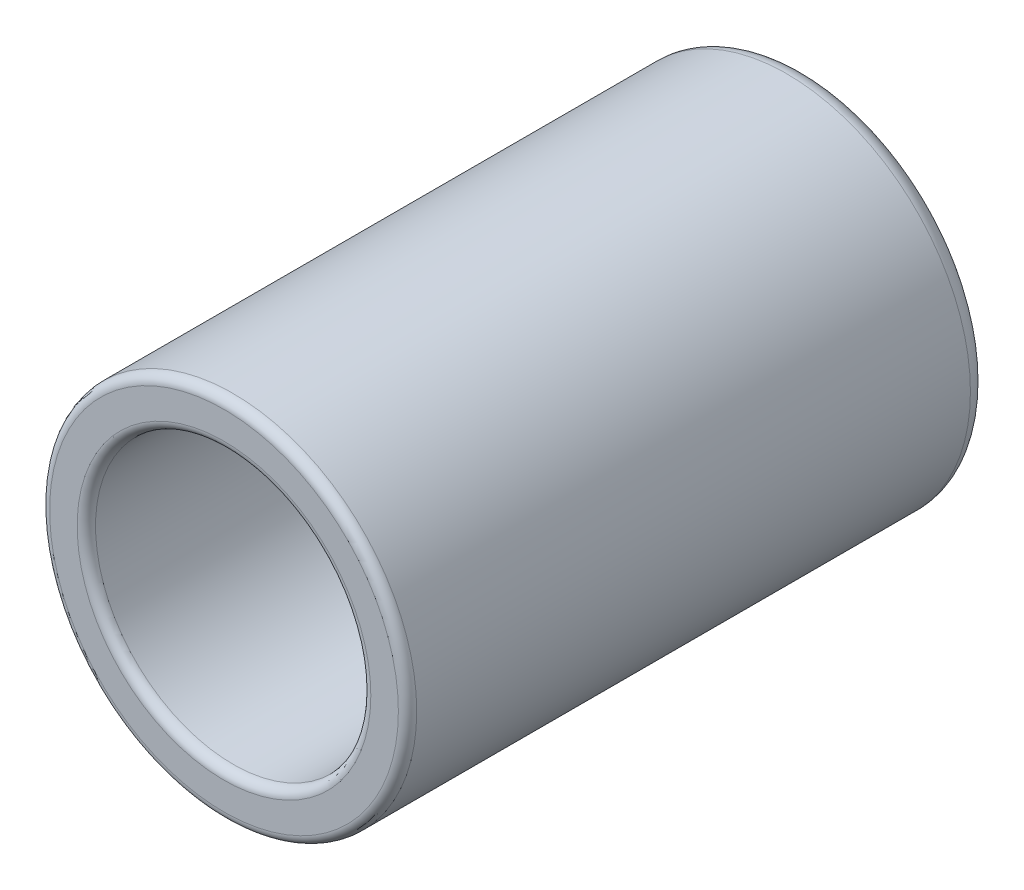
SolidWorks part; units mm, degrees
ref_plane "Płaszczyzna przednia" through (0, 0, 0) normal (0, 0, 1) x (1, 0, 0)
ref_plane "Płaszczyzna górna" through (0, 0, 0) normal (0, 1, 0) x (1, 0, 0)
ref_plane "Płaszczyzna prawa" through (0, 0, 0) normal (1, 0, 0) x (0, 0, -1)
sketch "Sketch1" plane through (0, 0, 0) normal (0, 0, 1) x (1, 0, 0)
  circle A0 centre (0, 0) radius 3
  dimension "D1" = 6
extrude "Boss-Extrude1" add sketch "Sketch1" along normal blind 9.5
sketch "Sketch2" plane through (0, 0, 9.5) normal (0, 0, 1) x (1, 0, 0)
  circle A0 centre (0, 0) radius 2.25
  dimension "D1" = 4.5
extrude "Cut-Extrude1" cut sketch "Sketch2" against normal blind 3.5
sketch "Sketch3" plane through (0, 0, 6) normal (0, 0, 1) x (1, 0, 0)
  circle A0 centre (0, 0) radius 1.25
  dimension "D1" = 2.5
extrude "Cut-Extrude2" cut sketch "Sketch3" against normal up to surface (6 mm away) up to face at (3, 0, 0)
fillet "Fillet1" radius 0.15 2 edges at (2.25, 0, 9.5) (3, 0, 9.5)
fillet "Fillet2" radius 0.3 1 edges at (3, 0, 0)
